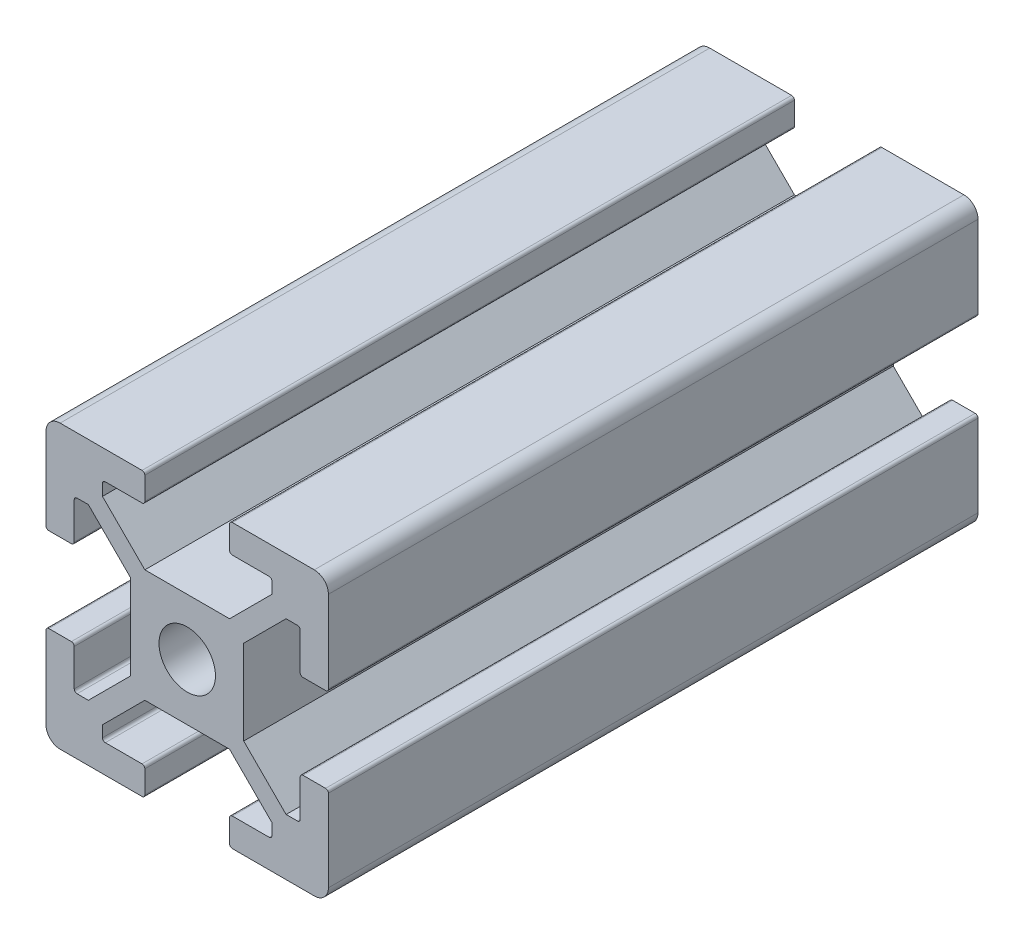
SolidWorks part; units mm, degrees
ref_plane "Front Plane" through (0, 0, 0) normal (0, 0, 1) x (1, 0, 0)
ref_plane "Top Plane" through (0, 0, 0) normal (0, 1, 0) x (1, 0, 0)
ref_plane "Right Plane" through (0, 0, 0) normal (1, 0, 0) x (0, 0, -1)
sketch "Sketch1" plane through (0, 0, 0) normal (0, 0, 1) x (1, 0, 0)
  circle A28 centre (0, 0) radius 2
  point P0 (0, 0)
  line B0 (-3.2, 8) -> (-5.8005, 8)
  line B1 (-6.0005, 7.8005) -> (-6.0027, 7.0027)
  line B2 (-6.0027, 7.0027) -> (-3, 4)
  line B3 (-3, 4) -> (3, 4)
  line B4 (3, 4) -> (6.0027, 7.0027)
  line B5 (6.0027, 7.0027) -> (6.0005, 7.8005)
  line B6 (5.8005, 8) -> (3.2, 8)
  line B7 (3, 8.2) -> (3, 9.8)
  line B8 (3.2, 10) -> (9, 10)
  line B9 (10, 9) -> (10, 3.2)
  line B10 (9.8, 3) -> (8.2, 3)
  line B11 (8, 3.2) -> (8, 5.8005)
  line B12 (7.8005, 6.0005) -> (7.0027, 6.0027)
  line B13 (7.0027, 6.0027) -> (4, 3)
  line B14 (4, 3) -> (4, -3)
  line B15 (4, -3) -> (7.0027, -6.0027)
  line B16 (7.0027, -6.0027) -> (7.8005, -6.0005)
  line B17 (8, -5.8005) -> (8, -3.2)
  line B18 (8.2, -3) -> (9.8, -3)
  line B19 (10, -3.2) -> (10, -9)
  line B20 (9, -10) -> (3.2, -10)
  line B21 (3, -9.8) -> (3, -8.2)
  line B22 (3.2, -8) -> (5.8005, -8)
  line B23 (6.0005, -7.8005) -> (6.0027, -7.0027)
  line B24 (6.0027, -7.0027) -> (3, -4)
  line B25 (3, -4) -> (-3, -4)
  line B26 (-3, -4) -> (-6.0027, -7.0027)
  line B27 (-6.0027, -7.0027) -> (-6.0005, -7.8005)
  line B28 (-5.8005, -8) -> (-3.2, -8)
  line B29 (-3, -8.2) -> (-3, -9.8)
  line B30 (-3.2, -10) -> (-9, -10)
  line B31 (-10, -9) -> (-10, -3.2)
  line B32 (-9.8, -3) -> (-8.2, -3)
  line B33 (-8, -3.2) -> (-8, -5.8005)
  line B34 (-7.8005, -6.0005) -> (-7.0027, -6.0027)
  line B35 (-7.0027, -6.0027) -> (-4, -3)
  line B36 (-4, -3) -> (-4, 3)
  line B37 (-4, 3) -> (-7.0027, 6.0027)
  line B38 (-7.0027, 6.0027) -> (-7.8005, 6.0005)
  line B39 (-8, 5.8005) -> (-8, 3.2)
  line B40 (-8.2, 3) -> (-9.8, 3)
  line B41 (-10, 3.2) -> (-10, 9)
  line B42 (-9, 10) -> (-3.2, 10)
  line B43 (-3, 9.8) -> (-3, 8.2)
  line B44 (0, -4) -> (0, 4) construction
  line B45 (-4, 0) -> (4, 0) construction
  arc B46 (-5.8005, 8) -> (-6.0005, 7.8005) centre (-5.8005, 7.8) ccw
  arc B47 (6.0005, 7.8005) -> (5.8005, 8) centre (5.8005, 7.8) ccw
  arc B48 (3, 8.2) -> (3.2, 8) centre (3.2, 8.2) ccw
  arc B49 (3.2, 10) -> (3, 9.8) centre (3.2, 9.8) ccw
  arc B50 (10, 9) -> (9, 10) centre (9, 9) ccw
  arc B51 (9.8, 3) -> (10, 3.2) centre (9.8, 3.2) ccw
  arc B52 (8, 3.2) -> (8.2, 3) centre (8.2, 3.2) ccw
  arc B53 (8, 5.8005) -> (7.8005, 6.0005) centre (7.8, 5.8005) ccw
  arc B54 (7.8005, -6.0005) -> (8, -5.8005) centre (7.8, -5.8005) ccw
  arc B55 (8.2, -3) -> (8, -3.2) centre (8.2, -3.2) ccw
  arc B56 (10, -3.2) -> (9.8, -3) centre (9.8, -3.2) ccw
  arc B57 (9, -10) -> (10, -9) centre (9, -9) ccw
  arc B58 (3, -9.8) -> (3.2, -10) centre (3.2, -9.8) ccw
  arc B59 (3.2, -8) -> (3, -8.2) centre (3.2, -8.2) ccw
  arc B60 (5.8005, -8) -> (6.0005, -7.8005) centre (5.8005, -7.8) ccw
  arc B61 (-6.0005, -7.8005) -> (-5.8005, -8) centre (-5.8005, -7.8) ccw
  arc B62 (-3, -8.2) -> (-3.2, -8) centre (-3.2, -8.2) ccw
  arc B63 (-3.2, -10) -> (-3, -9.8) centre (-3.2, -9.8) ccw
  arc B64 (-10, -9) -> (-9, -10) centre (-9, -9) ccw
  arc B65 (-9.8, -3) -> (-10, -3.2) centre (-9.8, -3.2) ccw
  arc B66 (-8, -3.2) -> (-8.2, -3) centre (-8.2, -3.2) ccw
  arc B67 (-8, -5.8005) -> (-7.8005, -6.0005) centre (-7.8, -5.8005) ccw
  arc B68 (-7.8005, 6.0005) -> (-8, 5.8005) centre (-7.8, 5.8005) ccw
  arc B69 (-8.2, 3) -> (-8, 3.2) centre (-8.2, 3.2) ccw
  arc B70 (-10, 3.2) -> (-9.8, 3) centre (-9.8, 3.2) ccw
  arc B71 (-9, 10) -> (-10, 9) centre (-9, 9) ccw
  arc B72 (-3, 9.8) -> (-3.2, 10) centre (-3.2, 9.8) ccw
  arc B73 (-3.2, 8) -> (-3, 8.2) centre (-3.2, 8.2) ccw
  dimension "D1" = 4
sketch_block_instance "Block1-1"
sketch_block "Block1"
extrude "Boss-Extrude1" add sketch "Sketch1" along normal blind 46
